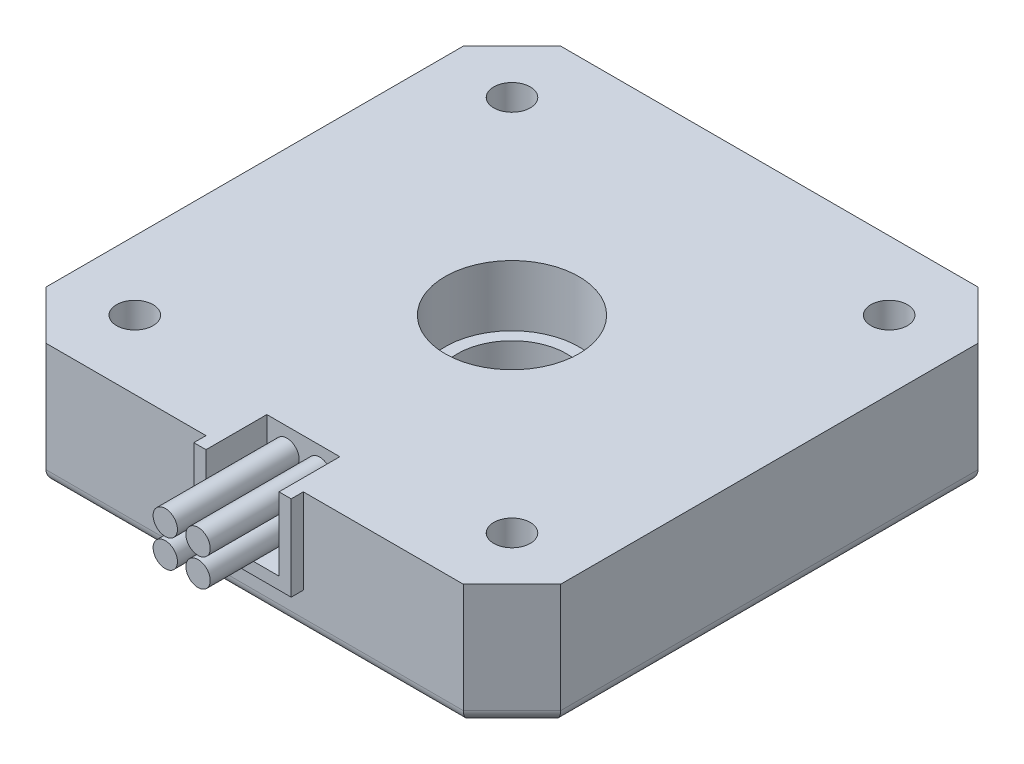
SolidWorks part; units mm, degrees
ref_plane "Front Plane" through (0, 0, 0) normal (0, 0, 1) x (1, 0, 0)
ref_plane "Top Plane" through (0, 0, 0) normal (0, 1, 0) x (1, 0, 0)
ref_plane "Right Plane" through (0, 0, 0) normal (1, 0, 0) x (0, 0, -1)
sketch "Sketch1" plane through (0, 0, 0) normal (0, 1, 0) x (1, 0, 0)
  line L0 (-21.15, 17.15) -> (-17.15, 21.15)
  line L1 (-17.15, 21.15) -> (17.15, 21.15)
  line L2 (-21.15, 17.15) -> (-21.15, -17.15)
  line L3 (-17.15, -21.15) -> (17.15, -21.15)
  line L4 (21.15, 17.15) -> (21.15, -17.15)
  line L5 (-21.15, 21.15) -> (21.15, -21.15) construction
  line L6 (-21.15, -21.15) -> (21.15, 21.15) construction
  line L7 (17.15, 21.15) -> (21.15, 17.15)
  line L8 (17.15, -21.15) -> (21.15, -17.15)
  line L9 (-21.15, -17.15) -> (-17.15, -21.15)
  point P0 (0, 0)
  dimension "D1" = 42.3
  dimension "D2" = 42.3
extrude "Boss-Extrude1" add sketch "Sketch1" along normal blind 10
sketch "Sketch2" plane through (0, 0, 0) normal (0, -1, 0) x (1, 0, 0)
  line L0 (0, 15.5) -> (0, -15.5) construction
  line L1 (-15.5, 15.5) -> (15.5, 15.5) construction
  line L2 (-15.5, 15.5) -> (-15.5, -15.5) construction
  line L3 (-15.5, -15.5) -> (15.5, -15.5) construction
  line L4 (15.5, 15.5) -> (15.5, -15.5) construction
  line L5 (-15.5, 15.5) -> (15.5, -15.5) construction
  line L6 (-15.5, -15.5) -> (15.5, 15.5) construction
  line L7 (-15.5, 0) -> (15.5, 0) construction
  circle A0 centre (-15.5, 15.5) radius 1.5
  circle A1 centre (15.5, 15.5) radius 1.5
  circle A2 centre (15.5, -15.5) radius 1.5
  circle A3 centre (-15.5, -15.5) radius 1.5
  point P0 (0, 0)
  dimension "D3" = 3
  dimension "D1" = 31
  dimension "D2" = 31
extrude "Cut-Extrude1" cut sketch "Sketch2" against normal blind 10
sketch "Sketch3" plane through (0, 0, 0) normal (0, -1, 0) x (1, 0, 0)
  line L0 (0, -15.5) -> (0, 15.5) construction
  line L1 (-15.5, -15.5) -> (15.5, -15.5) construction
  line L2 (-15.5, -15.5) -> (-15.5, 15.5) construction
  line L3 (-15.5, 15.5) -> (15.5, 15.5) construction
  line L4 (15.5, -15.5) -> (15.5, 15.5) construction
  line L5 (-15.5, -15.5) -> (15.5, 15.5) construction
  line L6 (-15.5, 15.5) -> (15.5, -15.5) construction
  line L7 (-15.5, 0) -> (15.5, 0) construction
  circle A0 centre (-15.5, 15.5) radius 3.1
  circle A1 centre (15.5, 15.5) radius 3.1
  circle A2 centre (15.5, -15.5) radius 3.1
  circle A3 centre (-15.5, -15.5) radius 3.1
  point P0 (0, 0)
  dimension "D1" = 6.2
extrude "Cut-Extrude2" cut sketch "Sketch3" against normal blind 3
fillet "Fillet1" radius 0.5 8 edges at (-15.5, 0, -12.4) (-15.5, 3, -12.4) (15.5, 0, -18.6) (15.5, 3, -18.6) (15.5, 3, 18.6) (15.5, 0, 18.6) (-15.5, 3, 12.4) (-15.5, 0, 12.4)
sketch "Sketch4" plane through (0, 0, 0) normal (0, -1, 0) x (1, 0, 0)
  circle A0 centre (0, 0) radius 4.5
  dimension "D1" = 9
extrude "Cut-Extrude3" cut sketch "Sketch4" against normal blind 10
fillet "Fillet2" radius 0.5 1 edges at (0, 0, -4.5)
sketch "Sketch5" plane through (0, 10, 0) normal (0, 1, 0) x (1, 0, 0)
  circle A0 centre (0, 0) radius 5.5
  dimension "D1" = 11
extrude "Cut-Extrude4" cut sketch "Sketch5" against normal blind 5
fillet "Fillet3" radius 1 8 edges at (-19.15, 0, -19.15) (-21.15, 0, 0) (-19.15, 0, 19.15) (0, 0, 21.15) (19.15, 0, 19.15) (21.15, 0, 0) (19.15, 0, -19.15) (0, 0, -21.15)
sketch "Sketch6" plane through (0, 0, 21.15) normal (0, 0, 1) x (1, 0, 0)
  line L0 (0, 10) -> (0, 4) construction
  line L4 (-4, 10) -> (-4, 3)
  line L5 (-4, 3) -> (4, 3)
  line L6 (4, 10) -> (4, 3)
  line L7 (-4, 10) -> (4, 3) construction
  line L8 (-4, 3) -> (4, 10) construction
  line L11 (-4, 10) -> (4, 10)
  point P5 (0, 6.5)
  point P10 (0, 4)
  dimension "D1" = 6
  dimension "D2" = 8
extrude "Boss-Extrude2" add sketch "Sketch6" along normal blind 1
sketch "Sketch7" plane through (0, 0, 22.15) normal (0, 0, 1) x (1, 0, 0)
  line L0 (0, 10) -> (0, 4) construction
  line L1 (4, 10) -> (-4, 10) construction
  line L2 (-3, 4) -> (3, 4)
  line L3 (-3, 4) -> (-3, 10)
  line L4 (-3, 10) -> (3, 10)
  line L5 (3, 10) -> (3, 4)
  point P8 (0, 4)
  dimension "D1" = 6
  dimension "D2" = 6
extrude "Cut-Extrude5" cut sketch "Sketch7" against normal blind 5
sketch "Sketch8" plane through (0, 0, 17.15) normal (0, 0, 1) x (1, 0, 0)
  line L0 (0, 10) -> (0, 4) construction
  line L1 (3, 10) -> (-3, 10) construction
  line L2 (-3, 4) -> (3, 4) construction
  line L3 (0, 7) -> (2.8653, 7) construction
  circle A1 centre (-1.3473, 5.8547) radius 1
  circle A2 centre (1.3473, 5.8547) radius 1
  circle A4 centre (1.3473, 8.1453) radius 1
  circle A5 centre (-1.3473, 8.1453) radius 1
extrude "Boss-Extrude4" add sketch "Sketch8" along normal blind 10
